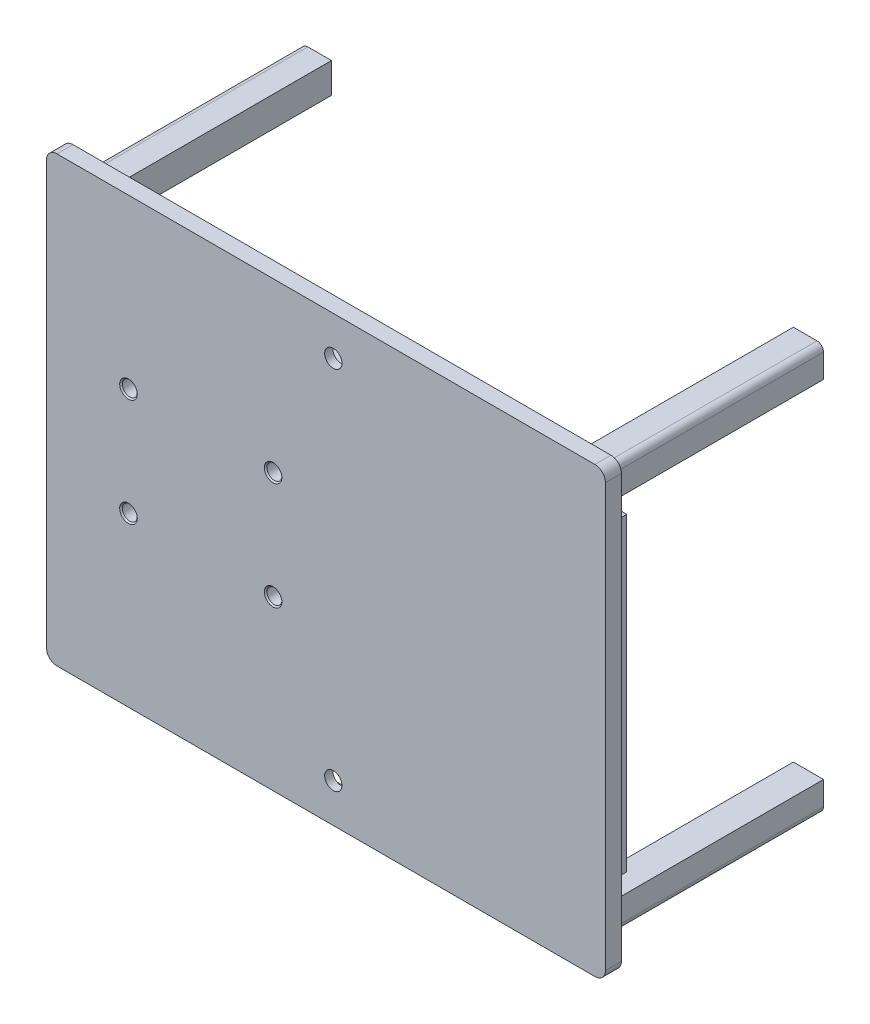
SolidWorks part; units mm, degrees
ref_plane "Alzado" through (0, 0, 0) normal (0, 0, 1) x (1, 0, 0)
ref_plane "Planta" through (0, 0, 0) normal (0, 1, 0) x (1, 0, 0)
ref_plane "Vista lateral" through (0, 0, 0) normal (1, 0, 0) x (0, 0, -1)
sketch "Croquis4" plane through (0, 0, 6.1) normal (0, 0, -1) x (-1, 0, 0)
  line L8 (-122.1, -80.5) -> (-122.1, 80.5) construction
  line L9 (-124.1, 82.5) -> (-329.1, 82.5) construction
  line L10 (-331.1, 80.5) -> (-331.1, -80.5) construction
  line L11 (-329.1, -82.5) -> (-124.1, -82.5) construction
  line L20 (-120.1, -80.5) -> (-120.1, 80.5)
  line L21 (-124.1, 84.5) -> (-329.1, 84.5)
  line L22 (-333.1, 80.5) -> (-333.1, -80.5)
  line L23 (-329.1, -84.5) -> (-124.1, -84.5)
  arc A8 (-122.1, 80.5) -> (-124.1, 82.5) centre (-124.1, 80.5) ccw construction
  arc A9 (-329.1, 82.5) -> (-331.1, 80.5) centre (-329.1, 80.5) ccw construction
  arc A10 (-331.1, -80.5) -> (-329.1, -82.5) centre (-329.1, -80.5) ccw construction
  arc A11 (-124.1, -82.5) -> (-122.1, -80.5) centre (-124.1, -80.5) ccw construction
  arc A20 (-120.1, 80.5) -> (-124.1, 84.5) centre (-124.1, 80.5) ccw
  arc A21 (-329.1, 84.5) -> (-333.1, 80.5) centre (-329.1, 80.5) ccw
  arc A22 (-333.1, -80.5) -> (-329.1, -84.5) centre (-329.1, -80.5) ccw
  arc A23 (-124.1, -84.5) -> (-120.1, -80.5) centre (-124.1, -80.5) ccw
extrude "Saliente-Extruir1" add sketch "Croquis4" along normal blind 3.1
sketch "Croquis5" plane through (0, 0, 3) normal (0, 0, -1) x (-1, 0, 0)
  line L17 (-326.1, 59) -> (-326.1, -59)
  line L18 (-324.1, 59) -> (-324.1, -59)
  line L19 (-324.1, -59) -> (-324.1, -75)
  line L24 (-323.6, -75.5) -> (-129.6, -75.5)
  line L25 (-129.1, -75) -> (-129.1, 75)
  line L26 (-129.6, 75.5) -> (-323.6, 75.5)
  line L27 (-324.1, 75) -> (-324.1, 59)
  line L37 (-323.6, -77.5) -> (-129.6, -77.5)
  line L38 (-326.1, -59) -> (-326.1, -75)
  line L39 (-209.1, -59) -> (-326.1, -59)
  line L40 (-209.1, -21.5) -> (-209.1, -59)
  line L41 (-213.1, -21.5) -> (-209.1, -21.5)
  line L42 (-213.1, -31.9511) -> (-213.1, -21.5)
  line L43 (-323.1, -31.9511) -> (-213.1, -31.9511)
  line L44 (-323.1, 31.9511) -> (-323.1, -31.9511)
  line L45 (-213.1, 31.9511) -> (-323.1, 31.9511)
  line L46 (-213.1, 21.5) -> (-213.1, 31.9511)
  line L47 (-209.1, 21.5) -> (-213.1, 21.5)
  line L48 (-209.1, 59) -> (-209.1, 21.5)
  line L49 (-326.1, 59) -> (-209.1, 59)
  line L50 (-326.1, 75) -> (-326.1, 59)
  line L51 (-129.6, 77.5) -> (-323.6, 77.5)
  line L52 (-127.1, -75) -> (-127.1, 75)
  line L53 (-323.6, -77.5) -> (-129.6, -77.5)
  line L54 (-326.1, -59) -> (-326.1, -75)
  line L66 (-326.1, 75) -> (-326.1, 59)
  line L67 (-129.6, 77.5) -> (-323.6, 77.5)
  line L68 (-127.1, -75) -> (-127.1, 75)
  arc A8 (-326.1, -75) -> (-323.6, -77.5) centre (-323.6, -75) ccw
  arc A9 (-323.6, 77.5) -> (-326.1, 75) centre (-323.6, 75) ccw
  arc A10 (-127.1, 75) -> (-129.6, 77.5) centre (-129.6, 75) ccw
  arc A11 (-129.6, -77.5) -> (-127.1, -75) centre (-129.6, -75) ccw
  arc A12 (-326.1, -75) -> (-323.6, -77.5) centre (-323.6, -75) ccw
  arc A13 (-323.6, 77.5) -> (-326.1, 75) centre (-323.6, 75) ccw
  arc A14 (-127.1, 75) -> (-129.6, 77.5) centre (-129.6, 75) ccw
  arc A15 (-129.6, -77.5) -> (-127.1, -75) centre (-129.6, -75) ccw
  arc A16 (-324.1, -75) -> (-323.6, -75.5) centre (-323.6, -75) ccw
  arc A17 (-129.6, -75.5) -> (-129.1, -75) centre (-129.6, -75) ccw
  arc A18 (-129.1, 75) -> (-129.6, 75.5) centre (-129.6, 75) ccw
  arc A19 (-323.6, 75.5) -> (-324.1, 75) centre (-323.6, 75) ccw
  dimension "D1" = 0
  dimension "D2" = 2
extrude "Saliente-Extruir2" add sketch "Croquis5" along normal blind 3 separate body
sketch "Croquis6" plane through (0, 0, 3) normal (0, 0, -1) x (-1, 0, 0)
  line L4 (-120.1, -80.5) -> (-120.1, 80.5)
  line L5 (-124.1, 84.5) -> (-329.1, 84.5)
  line L6 (-333.1, 80.5) -> (-333.1, -80.5)
  line L7 (-329.1, -84.5) -> (-124.1, -84.5)
  line L8 (-120.1, -80.5) -> (-120.1, 80.5)
  line L9 (-124.1, 84.5) -> (-329.1, 84.5)
  line L10 (-333.1, 80.5) -> (-333.1, -80.5)
  line L11 (-329.1, -84.5) -> (-124.1, -84.5)
  line L12 (-122.1, -80.5) -> (-122.1, 80.5)
  line L13 (-124.1, 82.5) -> (-329.1, 82.5)
  line L14 (-331.1, 80.5) -> (-331.1, -80.5)
  line L15 (-329.1, -82.5) -> (-124.1, -82.5)
  line L16 (-122.1, -80.5) -> (-122.1, 80.5)
  line L17 (-124.1, 82.5) -> (-329.1, 82.5)
  line L18 (-331.1, 80.5) -> (-331.1, -80.5)
  line L19 (-329.1, -82.5) -> (-124.1, -82.5)
  arc A4 (-124.1, -84.5) -> (-120.1, -80.5) centre (-124.1, -80.5) ccw
  arc A5 (-120.1, 80.5) -> (-124.1, 84.5) centre (-124.1, 80.5) ccw
  arc A6 (-329.1, 84.5) -> (-333.1, 80.5) centre (-329.1, 80.5) ccw
  arc A7 (-333.1, -80.5) -> (-329.1, -84.5) centre (-329.1, -80.5) ccw
  arc A8 (-124.1, -84.5) -> (-120.1, -80.5) centre (-124.1, -80.5) ccw
  arc A9 (-120.1, 80.5) -> (-124.1, 84.5) centre (-124.1, 80.5) ccw
  arc A10 (-329.1, 84.5) -> (-333.1, 80.5) centre (-329.1, 80.5) ccw
  arc A11 (-333.1, -80.5) -> (-329.1, -84.5) centre (-329.1, -80.5) ccw
  arc A12 (-122.1, 80.5) -> (-124.1, 82.5) centre (-124.1, 80.5) ccw
  arc A13 (-329.1, 82.5) -> (-331.1, 80.5) centre (-329.1, 80.5) ccw
  arc A14 (-331.1, -80.5) -> (-329.1, -82.5) centre (-329.1, -80.5) ccw
  arc A15 (-124.1, -82.5) -> (-122.1, -80.5) centre (-124.1, -80.5) ccw
  arc A16 (-122.1, 80.5) -> (-124.1, 82.5) centre (-124.1, 80.5) ccw
  arc A17 (-329.1, 82.5) -> (-331.1, 80.5) centre (-329.1, 80.5) ccw
  arc A18 (-331.1, -80.5) -> (-329.1, -82.5) centre (-329.1, -80.5) ccw
  arc A19 (-124.1, -82.5) -> (-122.1, -80.5) centre (-124.1, -80.5) ccw
  dimension "D1" = 0
  dimension "D2" = 0
extrude "Saliente-Extruir3" add sketch "Croquis6" along normal blind 3
sketch "Croquis7" plane through (0, 0, 6.1) normal (0, 0, 1) x (1, 0, 0)
  circle A0 centre (206.45, 20.5) radius 2.2479 construction
  circle A1 centre (151.35, 20.5) radius 2.2479 construction
  circle A2 centre (151.35, -20.5) radius 2.2479 construction
  circle A3 centre (206.45, -20.5) radius 2.2479 construction
  circle A4 centre (206.45, 20.5) radius 2.2479
  circle A5 centre (151.35, 20.5) radius 2.2479
  circle A6 centre (151.35, -20.5) radius 2.2479
  circle A7 centre (206.45, -20.5) radius 2.2479
hole_wizard "Taladro de margen para M41" positions "Croquis8" profile "Croquis9" hole size "M4" standard "Ansi Metric"
sketch "Croquis8" plane through (0, 0, 6.1) normal (0, 0, 1) x (1, 0, 0)
  point P0 (151.35, 20.5)
  point P3 (206.45, 20.5)
  point P6 (206.45, -20.5)
  point P9 (151.35, -20.5)
sketch "Croquis9" plane through (151.35, 20.5, 6.1) normal (1, 0, 0) x (0, -1, 0)
  line L0 (0, 0) -> (0, 9.5519)
  line L1 (0, 9.5519) -> (2.25, 8.2)
  line L2 (2.25, 8.2) -> (2.25, 0)
  line L5 (2.25, 0) -> (0, 0)
  line L10 (0, 9.5519) -> (-2.25, 8.2) construction
  line L11 (0, -6.35) -> (0, 107.95) construction
  dimension "Diámetro de taladro" = 4.5
  dimension "Profundidad de taladro" = 8.2
  dimension "Ángulo de perforador" = 118
sketch "Croquis10" plane through (0, 0, 3) normal (0, 0, -1) x (-1, 0, 0)
  line L17 (-127.1, 77.5) -> (-138.6, 77.5)
  line L36 (-127.1, 77.5) -> (-127.1, 66)
  line L37 (-127.1, 66) -> (-138.6, 66)
  line L38 (-138.6, 77.5) -> (-138.6, 66)
  line L39 (-127.1, -77.5) -> (-138.6, -77.5)
  line L40 (-127.1, -77.5) -> (-127.1, -66)
  line L41 (-127.1, -66) -> (-138.6, -66)
  line L42 (-138.6, -77.5) -> (-138.6, -66)
  line L43 (-326.1, -77.5) -> (-314.6, -77.5)
  line L44 (-326.1, -77.5) -> (-326.1, -66)
  line L45 (-326.1, -66) -> (-314.6, -66)
  line L46 (-314.6, -77.5) -> (-314.6, -66)
  line L47 (-326.1, 77.5) -> (-314.6, 77.5)
  line L48 (-326.1, 77.5) -> (-326.1, 66)
  line L49 (-326.1, 66) -> (-314.6, 66)
  line L50 (-314.6, 77.5) -> (-314.6, 66)
  dimension "D1" = 11.5
extrude "Saliente-Extruir4" add sketch "Croquis10" along normal up to surface (87 mm away)
sketch "Croquis13" plane through (0, 0, 3) normal (0, 0, -1) x (-1, 0, 0)
  line L12 (-213.1, -55) -> (-323.1, -55)
  line L13 (-213.1, -21.5) -> (-213.1, -55)
  line L14 (-209.1, -21.5) -> (-213.1, -21.5)
  line L15 (-209.1, -59) -> (-209.1, -21.5)
  line L16 (-326.1, -59) -> (-209.1, -59)
  line L17 (-326.1, 59) -> (-326.1, -59)
  line L18 (-209.1, 59) -> (-326.1, 59)
  line L19 (-209.1, 21.5) -> (-209.1, 59)
  line L20 (-213.1, 21.5) -> (-209.1, 21.5)
  line L21 (-213.1, 55) -> (-213.1, 21.5)
  line L22 (-323.1, 55) -> (-213.1, 55)
  line L23 (-323.1, -55) -> (-323.1, 55)
  line L24 (-213.1, -55) -> (-323.1, -55)
  line L25 (-213.1, -21.5) -> (-213.1, -55)
  line L26 (-209.1, -21.5) -> (-213.1, -21.5)
  line L27 (-209.1, -59) -> (-209.1, -21.5)
  line L28 (-326.1, -59) -> (-209.1, -59)
  line L30 (-209.1, 59) -> (-326.1, 59)
  line L31 (-209.1, 21.5) -> (-209.1, 59)
  line L32 (-213.1, 21.5) -> (-209.1, 21.5)
  line L33 (-213.1, 55) -> (-213.1, 21.5)
  line L34 (-323.1, 55) -> (-213.1, 55)
  line L35 (-323.1, -55) -> (-323.1, 55)
  line L48 (-326.1, 59) -> (-326.1, -59)
  dimension "D1" = 0
extrude "Saliente-Extruir5" add sketch "Croquis13" along normal blind 12
sketch "Croquis14" plane through (0, 0, -84) normal (0, 0, -1) x (-1, 0, 0)
  line L0 (-127.1, -77.5) -> (-138.6, -66) construction
  line L1 (-127.1, 77.5) -> (-138.6, 66) construction
  line L2 (-314.6, 66) -> (-326.1, 77.5) construction
  line L3 (-314.6, -66) -> (-326.1, -77.5) construction
  line L4 (-127.1, 77.5) -> (-326.1, 77.5) construction
  line L5 (-326.1, 77.5) -> (-314.6, 77.5) construction
  line L6 (-138.6, 77.5) -> (-127.1, 77.5) construction
  line L7 (-314.6, -77.5) -> (-326.1, -77.5) construction
  circle A0 centre (-132.85, -71.75) radius 2
  circle A1 centre (-132.85, 71.75) radius 2
  circle A2 centre (-320.35, 71.75) radius 2
  circle A3 centre (-320.35, -71.75) radius 2
  dimension "D1" = 4
extrude "Cortar-Extruir1" cut sketch "Croquis14" against normal blind 6
chamfer "Chaflán1" distance 0.3 angle 45 4 edges at (318.35, 71.75, -84) (318.35, -71.75, -84) (130.85, -71.75, -84) (130.85, 71.75, -84)
sketch "Croquis15" plane through (0, 0, 6.1) normal (0, 0, 1) x (1, 0, 0)
  circle A0 centre (229.4, 69.675) radius 3 construction
  circle A1 centre (229.4, -69.675) radius 3 construction
  circle A2 centre (229.4, 69.675) radius 3
  circle A3 centre (229.4, -69.675) radius 3
hole_wizard "Taladro de margen para M61" positions "Croquis16" profile "Croquis17" hole size "M6" standard "Ansi Metric"
sketch "Croquis16" plane through (0, 0, 6.1) normal (0, 0, 1) x (1, 0, 0)
  point P0 (229.4, 69.675)
  point P3 (229.4, -69.675)
sketch "Croquis17" plane through (229.4, 69.675, 6.1) normal (1, 0, 0) x (0, -1, 0)
  line L0 (0, 0) -> (0, 10.1828)
  line L1 (0, 10.1828) -> (3.3, 8.2)
  line L2 (3.3, 8.2) -> (3.3, 0)
  line L5 (3.3, 0) -> (0, 0)
  line L10 (0, 10.1828) -> (-3.3, 8.2) construction
  line L11 (0, -6.35) -> (0, 107.95) construction
  dimension "Diámetro de taladro" = 6.6
  dimension "Profundidad de taladro" = 8.2
  dimension "Ángulo de perforador" = 118
sketch "Croquis18" plane through (0, 0, -9) normal (0, 0, -1) x (-1, 0, 0)
  line L17 (-213.1, -55) -> (-213.1, -21.5) construction
  line L18 (-213.1, -55) -> (-323.1, -55) construction
  line L19 (-323.1, -55) -> (-323.1, 55) construction
  line L20 (-323.1, 55) -> (-213.1, 55) construction
  line L21 (-213.1, 21.5) -> (-213.1, 55) construction
  line L22 (-212.6, 21.5) -> (-212.6, 55.5)
  line L23 (-212.6, 55.5) -> (-323.6, 55.5)
  line L24 (-323.6, 55.5) -> (-323.6, -55.5)
  line L25 (-323.6, -55.5) -> (-212.6, -55.5)
  line L26 (-212.6, -55.5) -> (-212.6, -21.5)
  line L27 (-212.6, 21.5) -> (-212.6, 55.5)
  line L28 (-212.6, 55.5) -> (-323.6, 55.5)
  line L29 (-323.6, 55.5) -> (-323.6, -55.5)
  line L30 (-323.6, -55.5) -> (-212.6, -55.5)
  line L31 (-212.6, -55.5) -> (-212.6, -21.5)
  line L32 (-213.1, -55) -> (-213.1, -21.5)
  line L33 (-213.1, -55) -> (-323.1, -55)
  line L34 (-323.1, -55) -> (-323.1, 55)
  line L35 (-323.1, 55) -> (-213.1, 55)
  line L36 (-213.1, 21.5) -> (-213.1, 55)
  line L37 (-212.6, -21.5) -> (-213.1, -21.5)
  line L38 (-212.6, 21.5) -> (-213.1, 21.5)
  dimension "D1" = 0.5
extrude "Cortar-Extruir3" cut sketch "Croquis18" against normal up to surface (12 mm away) up to face at (229.4, 72.975, 3)
fillet "Redondeo1" radius 2.5 4 edges at (127.1, 77.5, -40.5) (326.1, 77.5, -40.5) (326.1, -77.5, -40.5) (127.1, -77.5, -40.5)
sketch "Croquis19" plane through (0, 0, 3) normal (0, 0, -1) x (-1, 0, 0)
  line L0 (-212.6, -21.5) -> (-212.6, -55.5) construction
  line L1 (-212.6, 55.5) -> (-212.6, 21.5) construction
  circle A0 centre (-206.45, -20.5) radius 2.25 construction
  circle A1 centre (-151.35, -20.5) radius 6.15
  circle A2 centre (-151.35, 20.5) radius 6.15
  circle A3 centre (-206.45, 20.5) radius 6.15
  circle A4 centre (-206.45, -20.5) radius 6.15
extrude "Saliente-Extruir6" add sketch "Croquis19" along normal up to surface (12 mm away) up to face at (248.85, 0, -9)
sketch "Croquis20" plane through (0, 0, 6.1) normal (0, 0, 1) x (1, 0, 0)
  circle A0 centre (151.35, -20.5) radius 2.25 construction
  circle A1 centre (206.45, -20.5) radius 2.25 construction
  circle A2 centre (206.45, 20.5) radius 2.25 construction
  circle A3 centre (151.35, 20.5) radius 2.25 construction
  circle A4 centre (151.35, -20.5) radius 2.25 construction
  circle A5 centre (206.45, -20.5) radius 2.25 construction
  circle A6 centre (206.45, 20.5) radius 2.25 construction
  circle A7 centre (151.35, 20.5) radius 2.25 construction
  circle A8 centre (151.35, -20.5) radius 2.85
  circle A9 centre (206.45, -20.5) radius 2.85
  circle A10 centre (206.45, 20.5) radius 2.85
  circle A11 centre (151.35, 20.5) radius 2.85
  dimension "D1" = 0.6
extrude "Cortar-Extruir4" cut sketch "Croquis20" against normal blind 8.2
chamfer "Chaflán2" distance 0.5 angle 45 4 edges at (209.3, 20.5, 6.1) (154.2, 20.5, 6.1) (154.2, -20.5, 6.1) (209.3, -20.5, 6.1)
